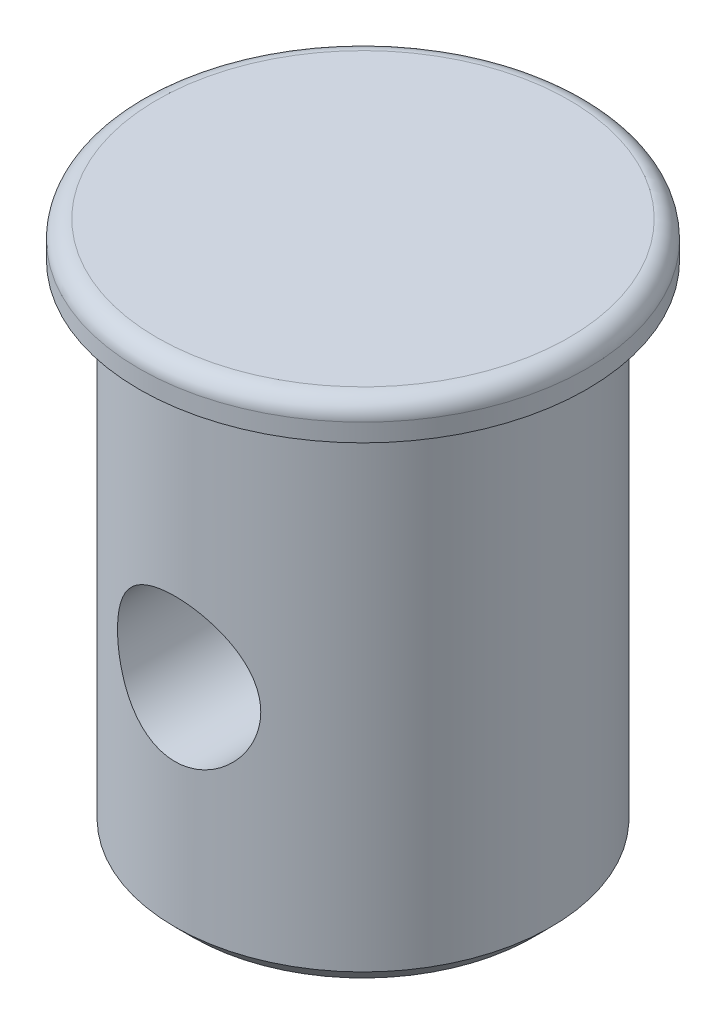
SolidWorks part; units mm, degrees
ref_plane "Спереди" through (0, 0, 0) normal (0, 0, 1) x (1, 0, 0)
ref_plane "Сверху" through (0, 0, 0) normal (0, 1, 0) x (1, 0, 0)
ref_plane "Справа" through (0, 0, 0) normal (1, 0, 0) x (0, 0, -1)
sketch "Эскиз1" plane through (0, 0, 0) normal (0, 1, 0) x (1, 0, 0)
  circle A0 centre (0, 0) radius 10.5
  dimension "D1" = 21
extrude "Бобышка-Вытянуть1" add sketch "Эскиз1" along normal blind 28
sketch "Эскиз2" plane through (0, 28, 0) normal (0, 1, 0) x (1, 0, 0)
  circle A0 centre (0, 0) radius 12.5
extrude "Бобышка-Вытянуть2" add sketch "Эскиз2" along normal blind 2
fillet "Скругление1" radius 1 1 edges at (0, 30, 12.5)
chamfer "Фаска1" distance 1 angle 45 1 edges at (0, 0, 10.5)
sketch "Эскиз3" plane through (0, 0, 0) normal (0, 0, 1) x (1, 0, 0)
  circle A0 centre (0, 13) radius 4
  dimension "D1" = 13
  dimension "D2" = 8
extrude "Вырез-Вытянуть1" cut sketch "Эскиз3" against normal through all and the other way through all
